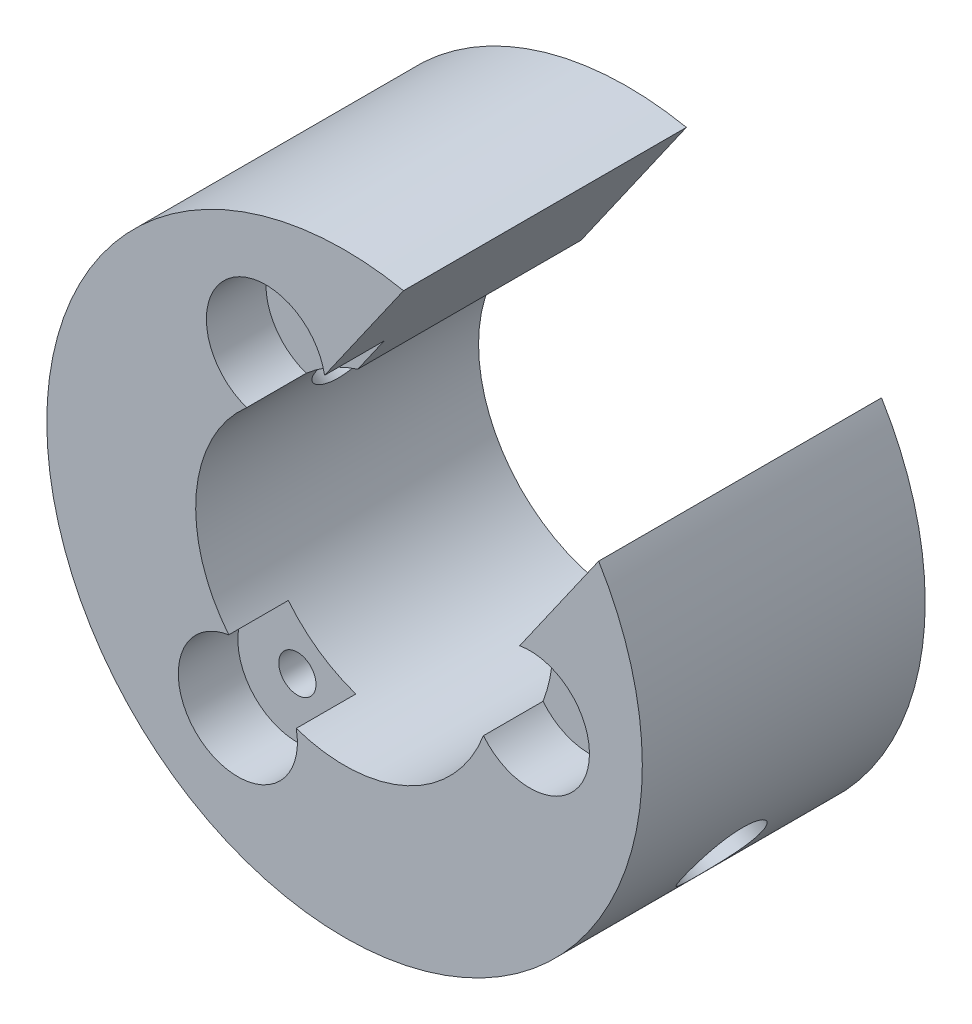
SolidWorks part; units mm, degrees
ref_plane "Front Plane" through (0, 0, 0) normal (0, 0, 1) x (1, 0, 0)
ref_plane "Top Plane" through (0, 0, 0) normal (0, 1, 0) x (1, 0, 0)
ref_plane "Right Plane" through (0, 0, 0) normal (1, 0, 0) x (0, 0, -1)
sketch "Sketch1" plane through (0, 0, 0) normal (0, 0, 1) x (1, 0, 0)
  line L0 (-12.0579, -7.1225) -> (-8.474, -2.0041) construction
  line L2 (-10.0298, 2.7476) -> (-6.4937, 7.7978)
  line L3 (-3.4766, -1.841) -> (0.0596, 3.2092)
  line L5 (-8.474, -2.0041) -> (-3.2171, 5.5035) construction
  line L6 (-6.4937, 7.7978) -> (0.0596, 3.2092) construction
  circle A1 centre (-11.1147, 3.6589) radius 0.625
  circle A2 centre (-2.2493, -2.5487) radius 0.625
  circle A3 centre (-12.0579, -7.1225) radius 0.625
  arc A5 (-10.0298, 2.7476) -> (-3.4766, -1.841) centre (-8.474, -2.0041) ccw
  arc A6 (-6.4937, 7.7978) -> (0.0596, 3.2092) centre (-8.474, -2.0041) ccw
  dimension "D2" = 8
  dimension "D3" = 1.25
  dimension "D4" = 1.25
  dimension "D5" = 1.25
  dimension "D8" = 5.663
  dimension "D14" = 10
  dimension "D15" = 20
  dimension "D6" = 8.474
  dimension "D7" = 2.0041
  dimension "D9" = 2.6407
  dimension "D10" = 3.5839
  dimension "D11" = 5.1184
  dimension "D12" = 6.2246
  dimension "D13" = 0.5446
extrude "Boss-Extrude1" add sketch "Sketch1" along normal blind 9.5
sketch "Sketch2" plane through (0, 0, 9.5) normal (0, 0, 1) x (1, 0, 0)
  line L0 (-12.0579, -7.1225) -> (-2.2493, -2.5487) construction
  line L1 (-2.2493, -2.5487) -> (-11.1147, 3.6589) construction
  line L2 (-11.1147, 3.6589) -> (-12.0579, -7.1225) construction
  line L4 (-8.4757, -2.0239) -> (-14.2016, -10.2014) construction
  line L7 (-16.659, 3.7061) -> (-0.2923, -7.754) construction
  circle A0 centre (-8.4757, -2.0239) radius 6.2484
  arc A3 (-6.4937, 7.7978) -> (0.0596, 3.2092) centre (-8.474, -2.0041) ccw construction
  dimension "D1" = 12.4968
ref_plane "Plane1" through (-12.936, 9.0579, 0) normal (-0.8192, 0.5736, 0) x (0, 0, 1)
sketch "Sketch3" plane through (-12.936, 9.0579, 0) normal (-0.8192, 0.5736, 0) x (0, 0, 1)
  line L4 (0, 2.663) -> (0, -16.5021) construction
  circle A1 centre (5, -6.5193) radius 1.325
  dimension "D1" = 5
  dimension "D2" = 2.65
extrude "Cut-Extrude1" cut sketch "Sketch3" against normal through all both and the other way through all
sketch "Sketch6" plane through (0, 0, 0) normal (0, 0, -1) x (-1, 0, 0)
  circle A0 centre (11.1147, 3.6589) radius 2
  circle A1 centre (12.0579, -7.1225) radius 2
  circle A2 centre (2.2493, -2.5487) radius 2
  dimension "D1" = 4
  dimension "D2" = 4
  dimension "D3" = 4
extrude "Cut-Extrude2" cut sketch "Sketch6" along normal blind 2 from surface at -9.5 starting at face at (-1.6243, -2.5487, 9.5)
